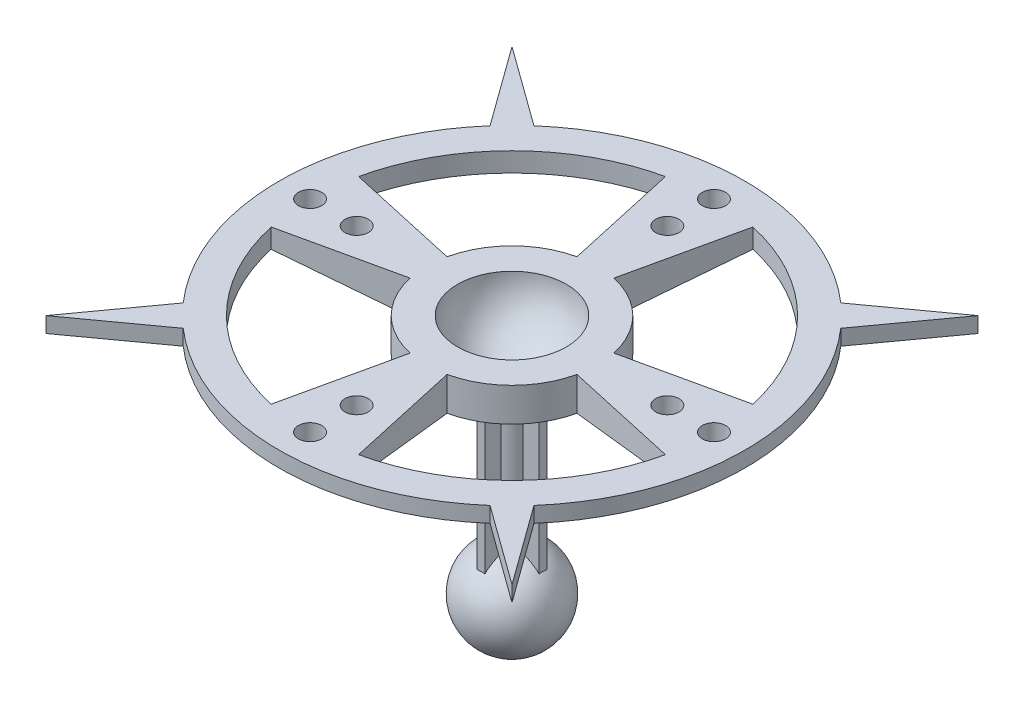
SolidWorks part; units mm, degrees
ref_plane "Front Plane" through (0, 0, 0) normal (0, 0, 1) x (1, 0, 0)
ref_plane "Top Plane" through (0, 0, 0) normal (0, 1, 0) x (1, 0, 0)
ref_plane "Right Plane" through (0, 0, 0) normal (1, 0, 0) x (0, 0, -1)
sketch "Sketch1" plane through (0, 0, 0) normal (1, 0, 0) x (0, 0, -1)
  line L0 (0, 4) -> (0, 0) construction
  line L1 (0, 0) -> (0, -8.5)
  line L2 (0, -8.5) -> (0, -11.5) construction
  line L3 (-4, 4) -> (-15, 4)
  line L4 (-15, 4) -> (-15, 3)
  line L5 (-15, 3) -> (-3.1588, 1.5461)
  line L6 (-4, 4) -> (-3.5, 4)
  line L7 (0, 0.127) -> (-1, 0.127) construction
  line L8 (1, 0.127) -> (1, -8.6716) construction
  line L9 (0, -8.6716) -> (-1, -8.6716) construction
  line L10 (-1, 0.127) -> (-1, -8.6716)
  line L11 (0, -14.5) -> (0, -8.5)
  line L12 (0, 0.5) -> (0, 0)
  line L13 (1, 0.127) -> (0, 0.127) construction
  line L14 (1, -8.6716) -> (0, -8.6716) construction
  line L15 (0, 10.6343) -> (0, 14.716) construction
  arc A0 (-1, -8.6716) -> (0, -14.5) centre (0, -11.5) ccw
  arc A1 (-3.1588, 1.5461) -> (-1, 0.127) centre (0, 4) ccw
  arc A2 (-3.5, 4) -> (0, 0.5) centre (0, 4) ccw
  arc A3 (0, 0) -> (1, 0.127) centre (0, 4) ccw construction
  arc A4 (0, 0.5) -> (-3.5, 4) centre (0, 4) ccw construction
  circle A5 centre (0, 4) radius 3.5 construction
  arc A6 (1, 0.127) -> (-4, 4) centre (0, 4) ccw construction
  circle A7 centre (0, 4) radius 4 construction
  arc A8 (-1, 0.127) -> (0, 0) centre (0, 4) ccw construction
  arc A9 (0, -14.5) -> (1, -8.6716) centre (0, -11.5) ccw construction
  arc A10 (1, -8.6716) -> (0, -8.5) centre (0, -11.5) ccw construction
  arc A11 (-4, 4) -> (-3.1588, 1.5461) centre (0, 4) ccw construction
  arc A12 (0, -8.5) -> (-1, -8.6716) centre (0, -11.5) ccw construction
  point P11 (3.8252, 5.1695)
  point P18 (0, -11.5)
  point P20 (3.5, 4)
  dimension "D1" = 8.5
  dimension "D2" = 4
  dimension "D3" = 3
  dimension "D5" = 11
  dimension "D6" = 1
  dimension "D7" = 97
  dimension "D8" = 2
  dimension "D4" = 0.5
revolve "Revolve1" add sketch "Sketch1" angle 360 about L15
sketch "Sketch2" plane through (0, 4, 0) normal (0, 1, 0) x (1, 0, 0)
  line L0 (-15, 0) -> (15, 0) construction
  line L1 (0.0131, 15) -> (0.0132, -15) construction
  circle A0 centre (0, 0) radius 0.5
  circle A1 centre (-9.5, 0) radius 0.75
  circle A2 centre (1.0131, -5.5) radius 0.75
  circle A3 centre (0.0132, -9.5) radius 0.75
  circle A4 centre (0.0132, 9.5) radius 0.75
  circle A5 centre (9.5263, 0) radius 0.75
  circle A6 centre (-5.4864, 1) radius 0.75
  circle A7 centre (-5.4864, -1) radius 0.75
  circle A8 centre (-0.9869, -5.5) radius 0.75
  circle A9 centre (5.5126, -1) radius 0.75
  circle A10 centre (5.5126, 1) radius 0.75
  circle A11 centre (1.0131, 5.5) radius 0.75
  circle A12 centre (-0.9869, 5.5) radius 0.75
  circle A13 centre (0, 0) radius 15 construction
  dimension "D1" = 1
  dimension "D3" = 1.5
  dimension "D6" = 1.5
  dimension "D9" = 1.5
  dimension "D2" = 9.5
  dimension "D4" = 5.5
  dimension "D5" = 9.5
  dimension "D7" = 1
  dimension "D8" = 5.4995
  dimension "D10" = 1
extrude "Cut-Extrude1" [suppressed] cut sketch "Sketch2" against normal blind 30 contours A7 | A1 | A3 | A8 | A2 | A9 | A10 | A5 | A11 | A12 | A4 | A6
sketch "Sketch3" plane through (0, 0, 0) normal (0, 1, 0) x (1, 0, 0)
  line L1 (-0.25, 2) -> (0.25, 2)
  line L2 (-0.25, 2) -> (-0.25, -2)
  line L3 (-0.25, -2) -> (0.25, -2)
  line L4 (0.25, 2) -> (0.25, -2)
  line L5 (0, -2) -> (0, 2) construction
  line L6 (-0.25, 0) -> (0.25, 0) construction
  line L7 (-2, 0.25) -> (2, 0.25)
  line L8 (-2, 0.25) -> (-2, -0.25)
  line L9 (-2, -0.25) -> (2, -0.25)
  line L10 (2, 0.25) -> (2, -0.25)
  line L11 (0, -0.25) -> (0, 0.25) construction
  line L12 (-2, 0) -> (2, 0) construction
  point P0 (0, 0)
  point P4 (0, 0)
  point P6 (0, 0)
  dimension "D1" = 0.5
  dimension "D2" = 4
  dimension "D3" = 0.5
  dimension "D4" = 4
extrude "Boss-Extrude1" add sketch "Sketch3" against normal blind 13 and the other way up to surface contours L4 L3 L2 L1 | L9 L10 L7 L8
sketch "Sketch4" plane through (0, 4, 0) normal (0, 1, 0) x (1, 0, 0)
  line L0 (-13, 0) -> (13, 0) construction
  line L1 (-11.3896, 9.761) -> (11.3896, 9.761) construction
  line L2 (-11.3896, 9.761) -> (-11.3896, -9.761) construction
  line L3 (-11.3896, -9.761) -> (11.3896, -9.761) construction
  line L4 (11.3896, 9.761) -> (11.3896, -9.761) construction
  line L5 (0, -9.761) -> (0, 9.761) construction
  line L6 (-11.3896, 0) -> (11.3896, 0) construction
  line L7 (0, 13) -> (0, -13) construction
  line L8 (-1.1904, 5.3696) -> (0, 0) construction
  line L9 (1.1904, 5.3696) -> (0, 0) construction
  line L10 (-1.1904, -5.3696) -> (0, 0) construction
  line L11 (1.1904, -5.3696) -> (0, 0) construction
  line L12 (-3.2466, 14.6444) -> (-1.1904, 5.3696)
  line L13 (3.2466, 14.6444) -> (1.1904, 5.3696)
  line L14 (3.2466, -14.6444) -> (1.1904, -5.3696)
  line L15 (-3.2466, -14.6444) -> (-1.1904, -5.3696)
  line L16 (5.3696, 1.1904) -> (0, 0) construction
  line L17 (5.3696, -1.1904) -> (0, 0) construction
  line L18 (-5.3696, -1.1904) -> (0, 0) construction
  line L19 (-5.3696, 1.1904) -> (0, 0) construction
  line L20 (5.3696, 1.1904) -> (14.6444, 3.2466)
  line L21 (5.3696, -1.1904) -> (14.6444, -3.2466)
  line L22 (-5.3696, -1.1904) -> (-14.6444, -3.2466)
  line L23 (-5.3696, 1.1904) -> (-14.6444, 3.2466)
  circle A0 centre (0, 0) radius 15 construction
  circle A1 centre (0, 0) radius 15
  circle A2 centre (0, 0) radius 13
  circle A3 centre (0, 0) radius 5.5
  circle A4 centre (0, 0) radius 3.5
  circle A5 centre (0, 0) radius 6 construction
  circle A6 centre (0, 0) radius 3.5 construction
  circle A7 centre (13, 0) radius 0.75
  circle A8 centre (10, 0) radius 0.75
  circle A9 centre (0, 10) radius 0.75
  circle A10 centre (0, 13) radius 0.75
  circle A11 centre (0, -13) radius 0.75
  circle A12 centre (0, -10) radius 0.75
  circle A13 centre (-13, 0) radius 0.75
  circle A14 centre (-10, 0) radius 0.75
  point P0 (0, 0)
  point P12 (0, 0)
  point P13 (0, 0)
  point P14 (0, 0)
  point P27 (0, 0)
  point P28 (0, 0)
  point P53 (0, 0)
  point P59 (5.8578, 1.2986)
  point P61 (0, 0)
  point P62 (0, 0)
  point P63 (0, 0)
  point P64 (0, 0)
  dimension "D1" = 30
  dimension "D4" = 12
  dimension "D7" = 1.5
  dimension "D5" = 2
  dimension "D6" = 2
  dimension "D8" = 1.5
  dimension "D9" = 1.5
  dimension "D10" = 1.5
  dimension "D12" = 10
  dimension "D2" = 12.5
  dimension "D3" = 12.5
  dimension "D11" = 13
  dimension "D13" = 10
  dimension "D14" = 13
extrude "Cut-Extrude2" cut sketch "Sketch4" against normal blind 4 contours A3 L12 A2 L23 | A3 L22 A2 L15 | A3 L14 A2 L21 | A3 L20 A2 L13 | A13 | A14 | A9 | A10 | A12 | A11 | A8 | A7
sketch "Sketch5" plane through (0, 4, 0) normal (0, 1, 0) x (1, 0, 0)
  line L0 (-9.5626, 9.5626) -> (9.5626, -9.5626) construction
  line L1 (10.6066, 10.6066) -> (-10.6066, 10.6066) construction
  line L2 (10.6066, 10.6066) -> (10.6066, -10.6066) construction
  line L3 (10.6066, -10.6066) -> (-10.6066, -10.6066) construction
  line L4 (-10.6066, 10.6066) -> (-10.6066, -10.6066) construction
  line L5 (0, -10.6066) -> (0, 10.6066) construction
  line L6 (10.6066, 0) -> (-10.6066, 0) construction
  line L7 (13.6328, 13.6328) -> (-13.6328, -13.6328) construction
  line L8 (-9.8759, 11.2901) -> (-11.2901, 9.8759)
  line L9 (15, 15) -> (11.2901, 9.8759)
  line L10 (9.8759, 11.2901) -> (15, 15)
  line L11 (9.8759, 11.2901) -> (11.2901, 9.8759)
  line L12 (-28.261, -15) -> (27.3338, -15) construction
  line L13 (-25.98, 15) -> (25.98, 15) construction
  line L14 (-13.6328, 13.6328) -> (13.6328, -13.6328) construction
  line L15 (-15, 15) -> (-11.2901, 9.8759)
  line L16 (-9.8759, 11.2901) -> (-15, 15)
  line L17 (-9.8759, 11.2901) -> (-11.2901, 9.8759)
  line L18 (-9.5626, -9.5626) -> (9.5626, 9.5626) construction
  line L19 (-9.8759, -11.2901) -> (-15, -15)
  line L20 (-15, -15) -> (-11.2901, -9.8759)
  line L21 (-9.8759, -11.2901) -> (-11.2901, -9.8759)
  line L22 (9.8759, -11.2901) -> (15, -15)
  line L23 (15, -15) -> (11.2901, -9.8759)
  line L24 (9.8759, -11.2901) -> (11.2901, -9.8759)
  circle A0 centre (0, 0) radius 15 construction
  circle A1 centre (0, 0) radius 15 construction
  point P2 (0, 0)
  point P6 (0, 0)
  point P11 (0, 0)
  point P16 (0, 15)
  point P29 (-10.583, 10.583)
  point P40 (0, 0)
  point P42 (-25.98, 15)
  point P43 (-28.261, -15)
  point P44 (27.3338, -15)
  circle M19 centre (0, 0) radius 15
  dimension "D1" = 30
  dimension "D2" = 45
  dimension "D3" = 2
extrude "Boss-Extrude2" add sketch "Sketch5" against normal blind 1 contours L16 L15 M19 | L10 L9 M19 | L22 L23 M19 | L20 L19 M19
equation "\"D1@Sketch1\"=15-6.5"
